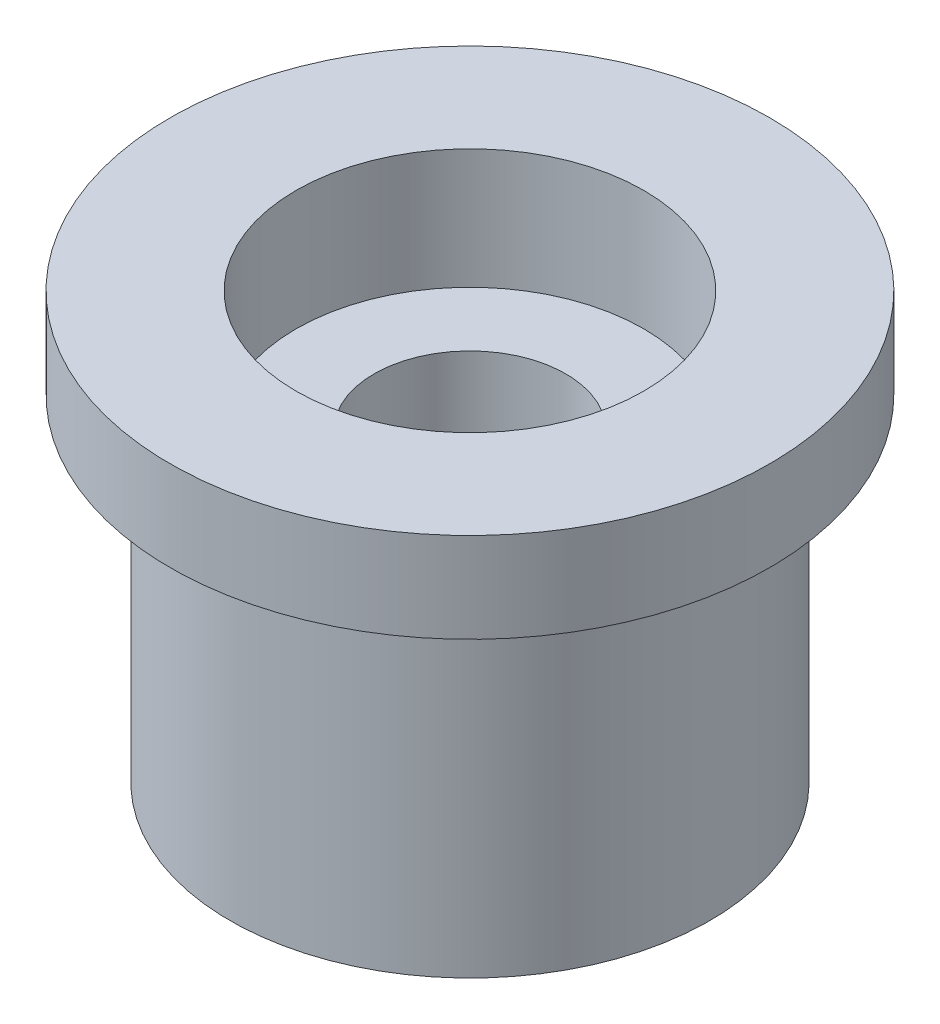
SolidWorks part; units mm, degrees
ref_plane "前视基准面" through (0, 0, 0) normal (0, 0, 1) x (1, 0, 0)
ref_plane "上视基准面" through (0, 0, 0) normal (0, 1, 0) x (1, 0, 0)
ref_plane "右视基准面" through (0, 0, 0) normal (1, 0, 0) x (0, 0, -1)
sketch "草图1" plane through (0, 0, 0) normal (0, 0, 1) x (1, 0, 0)
  line L0 (5, 7.1) -> (0, 7.1)
  line L1 (0, 7.1) -> (0, 5.6)
  line L2 (0, 5.6) -> (5, 5.6)
  line L3 (5, 5.6) -> (5, 7.1)
  line L4 (0, 7.1) -> (0, 5.6) construction
revolve "旋转1" add sketch "草图1" angle 360 about L4
sketch "草图2" plane through (0, 5.6, 0) normal (0, -1, 0) x (1, 0, 0)
  circle A0 centre (0, 0) radius 4
extrude "凸台-拉伸1" add sketch "草图2" along normal blind 5.6
sketch "草图3" plane through (0, 0, 0) normal (0, -1, 0) x (1, 0, 0)
  line L0 (-1.4789, 1.7615) -> (-1.8835, 2.4622)
  line L1 (-1.8835, -2.4622) -> (-1.4789, -1.7615)
  arc A0 (-1.8835, 2.4622) -> (-1.8835, -2.4622) centre (0, 0) ccw
  arc A1 (-1.4789, -1.7615) -> (-1.4789, 1.7615) centre (0, 0) cw
extrude "切除-拉伸1" cut sketch "草图3" against normal blind 4.3
sketch "草图4" plane through (0, 0, 0) normal (0, -1, 0) x (1, 0, 0)
  line L0 (3.0741, -0.4) -> (2.265, -0.4)
  line L1 (-0.7861, -2.1615) -> (-1.1906, -2.8622)
  arc A0 (2.265, -0.4) -> (-0.7861, -2.1615) centre (0, 0) cw
  arc A1 (-1.1906, -2.8622) -> (3.0741, -0.4) centre (0, 0) ccw
extrude "切除-拉伸2" cut sketch "草图4" against normal blind 4.3
sketch "草图5" plane through (0, 0, 0) normal (0, -1, 0) x (1, 0, 0)
  line L0 (2.265, 0.4) -> (3.0741, 0.4)
  line L1 (-1.1906, 2.8622) -> (-0.7861, 2.1615)
  arc A0 (3.0741, 0.4) -> (-1.1906, 2.8622) centre (0, 0) ccw
  arc A1 (-0.7861, 2.1615) -> (2.265, 0.4) centre (0, 0) cw
extrude "切除-拉伸3" cut sketch "草图5" against normal blind 4.3
hole_wizard "M3 六角头机械螺钉的柱形沉头孔1" positions "草图7" profile "草图6" counterbore size "M3" standard "ANSI Metric"
sketch "草图7" plane through (0, 7.1, 0) normal (0, 1, 0) x (1, 0, 0)
  point P0 (0, 0)
sketch "草图6" plane through (0, 7.1, 0) normal (1, 0, 0) x (0, 0, 1)
  line L0 (0, 0) -> (0, 7.1)
  line L1 (0, 7.1) -> (1.6, 7.1)
  line L3 (1.6, 7.1) -> (1.6, 2)
  line L4 (1.6, 2) -> (2.9, 2)
  line L5 (2.9, 2) -> (2.9, 0)
  line L7 (2.9, 0) -> (0, 0)
  line L11 (0, -6.35) -> (0, 107.95) construction
  dimension "通孔孔直径" = 3.2
  dimension "通孔孔深度" = 7.1
  dimension "柱形沉头孔直径" = 5.8
  dimension "柱形沉头孔深度" = 2
